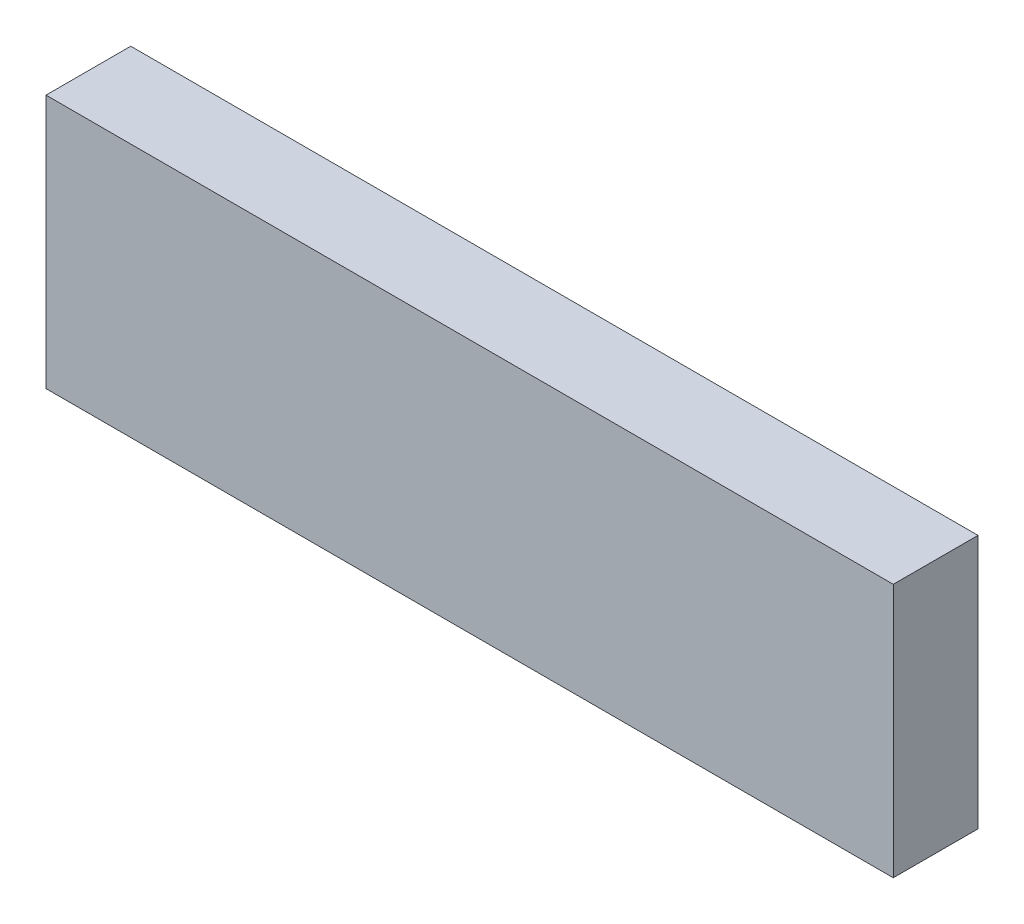
SolidWorks part; units mm, degrees
ref_plane "Front Plane" through (0, 0, 0) normal (0, 0, 1) x (1, 0, 0)
ref_plane "Top Plane" through (0, 0, 0) normal (0, 1, 0) x (1, 0, 0)
ref_plane "Right Plane" through (0, 0, 0) normal (1, 0, 0) x (0, 0, -1)
sketch "Sketch1" plane through (0, 0, 0) normal (0, 0, 1) x (1, 0, 0)
  line L1 (-250, 75) -> (250, 75)
  line L2 (-250, 75) -> (-250, -75)
  line L3 (-250, -75) -> (250, -75)
  line L4 (250, 75) -> (250, -75)
  line L5 (-250, 75) -> (250, -75) construction
  line L6 (-250, -75) -> (250, 75) construction
  point P0 (0, 0)
  dimension "D1" = 500
  dimension "D2" = 150
extrude "Boss-Extrude1" add sketch "Sketch1" along normal mid plane 50
